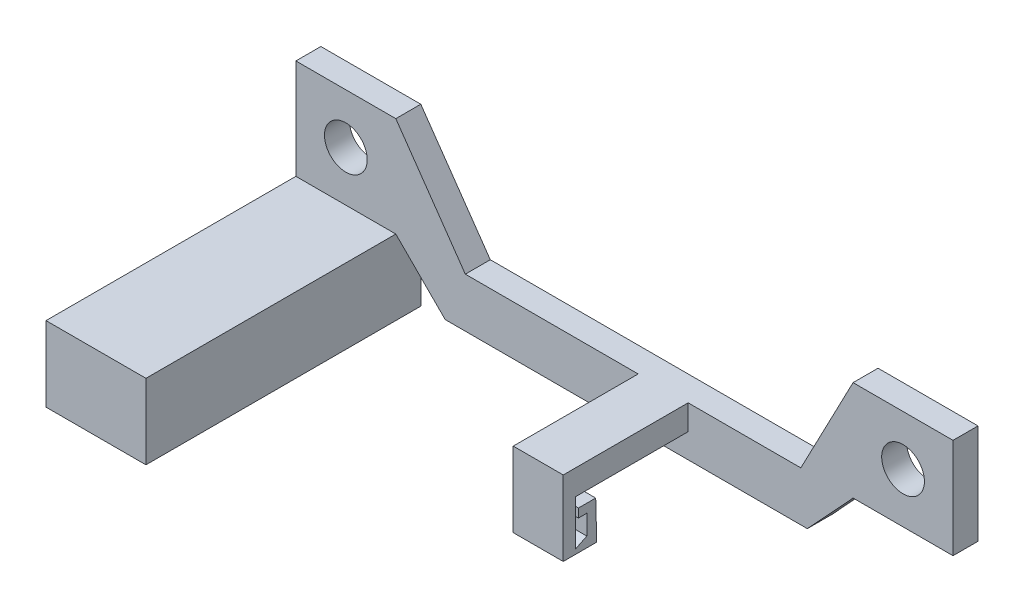
SolidWorks part; units mm, degrees
ref_plane "Front Plane" through (0, 0, 0) normal (0, 0, 1) x (1, 0, 0)
ref_plane "Top Plane" through (0, 0, 0) normal (0, 1, 0) x (1, 0, 0)
ref_plane "Right Plane" through (0, 0, 0) normal (1, 0, 0) x (0, 0, -1)
sketch "Sketch1" plane through (0, 0, 0) normal (0, 0, 1) x (1, 0, 0)
  line L1 (0, 5.08) -> (5.08, 5.08)
  line L3 (5.08, -5.08) -> (-5.08, -5.08)
  line L4 (-5.08, -5.08) -> (-5.08, 5.08)
  line L5 (-5.08, 5.08) -> (0, 5.08)
  line L7 (56.642, 5.08) -> (61.722, 5.08)
  line L8 (61.722, 5.08) -> (61.722, -5.08)
  line L9 (61.722, -5.08) -> (51.562, -5.08)
  line L11 (51.562, 5.08) -> (56.642, 5.08)
  line L12 (5.08, 5.08) -> (12.1453, -5.08)
  line L13 (12.1453, -5.08) -> (46.2524, -5.08)
  line L14 (46.2524, -5.08) -> (51.562, 5.08)
  line L15 (5.08, -5.08) -> (10.1021, -10.1021)
  line L16 (10.1021, -10.1021) -> (46.9108, -10.1021)
  line L17 (46.9108, -10.1021) -> (51.562, -5.08)
  line L18 (56.642, 5.08) -> (51.562, 5.08)
  circle A0 centre (0, 0) radius 2.1717
  circle A1 centre (56.642, 0) radius 2.1717
extrude "Boss-Extrude2" add sketch "Sketch1" along normal blind 2.54 contours L16 L17 L9 L8 L7 L11 L14 L13 L12 L1 L5 L4 L3 L15 A1 A0
sketch "Sketch2" plane through (0, 0, 2.54) normal (0, 0, 1) x (1, 0, 0)
  line L1 (-5.08, -5.08) -> (-5.08, -12.7)
  line L2 (-5.08, -12.7) -> (5.08, -12.7)
  line L3 (5.08, -12.7) -> (5.08, -5.08)
  line L4 (5.08, -5.08) -> (10.1021, -10.1021) construction
  line L5 (5.08, -5.08) -> (-5.08, -5.08)
extrude "Boss-Extrude3" add sketch "Sketch2" along normal blind 25.4 and the other way blind 2.54
sketch "Sketch3" plane through (0, 0, 2.54) normal (0, 0, 1) x (1, 0, 0)
  line L0 (-5.08, -0.8303) -> (29.718, -0.8303)
  line L1 (-5.08, -5.08) -> (-5.08, 5.08) construction
  line L8 (12.1453, -5.08) -> (46.2524, -5.08) construction
  line L9 (29.718, -5.08) -> (29.718, -7.62)
  line L10 (29.718, -7.62) -> (34.798, -7.62)
  line L11 (34.798, -7.62) -> (34.798, -5.08)
  line L12 (34.798, -5.08) -> (29.718, -5.08)
  line M14 (46.2524, -5.08) -> (12.1453, -5.08)
extrude "Boss-Extrude7" add sketch "Sketch3" along normal blind 12.7 contours L10 L11 L9 M14
sketch "Sketch5" plane through (34.798, 0, 0) normal (1, 0, 0) x (0, 0, -1)
  line L0 (-15.24, -7.62) -> (-15.24, -12.7)
  line L1 (-15.24, -12.7) -> (-13.97, -12.7)
  line L5 (-12.8411, -9.6464) -> (-13.6932, -9.6464)
  line L6 (-13.6932, -9.6464) -> (-13.6932, -8.7634)
  line L7 (-13.6932, -8.7634) -> (-11.938, -8.7634)
  line L8 (-13.97, -12.7) -> (-11.8348, -12.7)
  line L12 (-13.97, -9.6464) -> (-13.97, -7.62)
  line L13 (-15.24, -7.62) -> (-2.54, -7.62) construction
  line L14 (-12.8411, -9.6464) -> (-12.8411, -11.6585)
  line L15 (-13.97, -7.62) -> (-15.24, -7.62)
  line L16 (-12.8411, -11.6585) -> (-13.97, -12.2158)
  line L17 (-13.97, -12.2158) -> (-13.97, -9.6464)
  line L18 (-11.938, -8.7634) -> (-11.8348, -12.7)
extrude "Boss-Extrude8" add sketch "Sketch5" against normal blind 5.08
